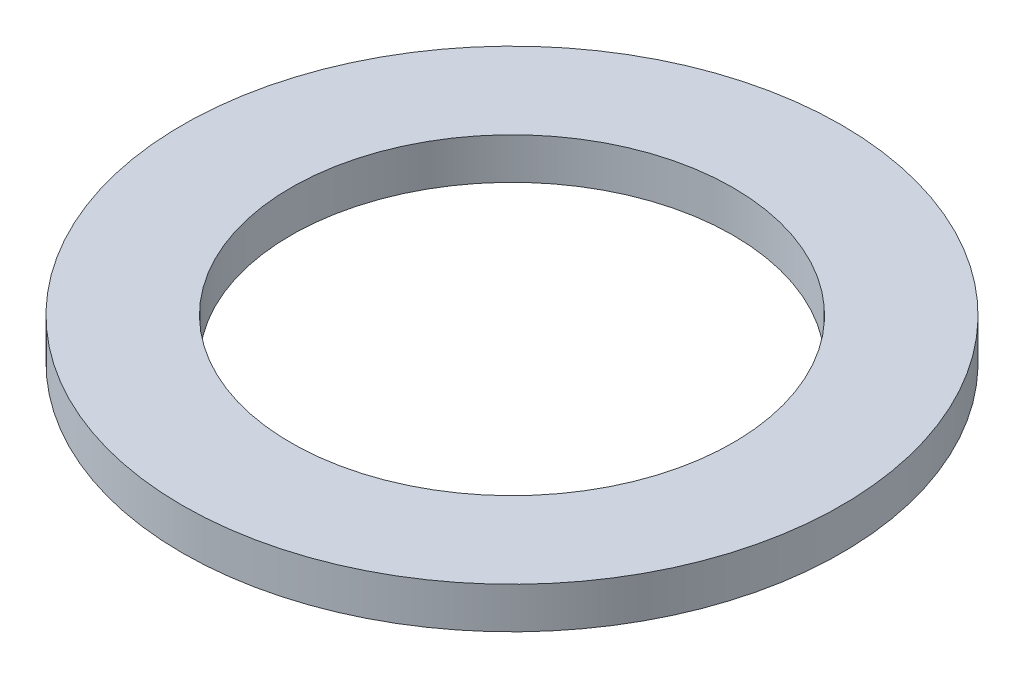
SolidWorks part; units mm, degrees
material "6061 Alloy"
ref_plane "Front Plane" through (0, 0, 0) normal (0, 0, 1) x (1, 0, 0)
ref_plane "Top Plane" through (0, 0, 0) normal (0, 1, 0) x (1, 0, 0)
ref_plane "Right Plane" through (0, 0, 0) normal (1, 0, 0) x (0, 0, -1)
sketch "Centering Ring Profile" plane through (0, 0, 0) normal (0, 1, 0) x (1, 0, 0)
  circle A0 centre (0, 0) radius 51.1048
  circle A1 centre (0, 0) radius 76.2
  dimension "D1" = 102.2096
  dimension "D2" = 152.4
extrude "Centering Ring Body" add sketch "Centering Ring Profile" along normal blind 9.525
equation "\"Ring Thickness\"= 0.375"
equation "\"Outer Diameter\"= 6"
equation "\"Inner Diameter\"= 4.024"
equation "\"D1@Centering Ring Profile\"=\"Inner Diameter\""
equation "\"D2@Centering Ring Profile\"=\"Outer Diameter\""
equation "\"D1@Centering Ring Body\"=\"Ring Thickness\""
